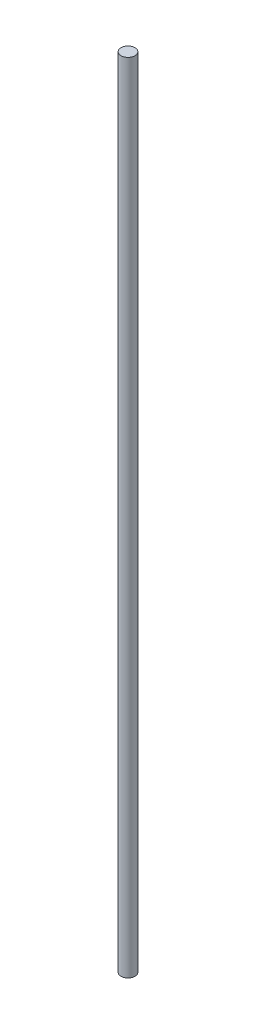
SolidWorks part; units mm, degrees
material "Carbon fibre"
ref_plane "Front Plane" through (0, 0, 0) normal (0, 0, 1) x (1, 0, 0)
ref_plane "Top Plane" through (0, 0, 0) normal (0, 1, 0) x (1, 0, 0)
ref_plane "Right Plane" through (0, 0, 0) normal (1, 0, 0) x (0, 0, -1)
sketch "Sketch1" plane through (0, 0, 0) normal (0, 1, 0) x (1, 0, 0)
  circle A0 centre (0, 0) radius 1.4
  dimension "D1" = 2.8
extrude "Boss-Extrude1" add sketch "Sketch1" along normal blind 160
